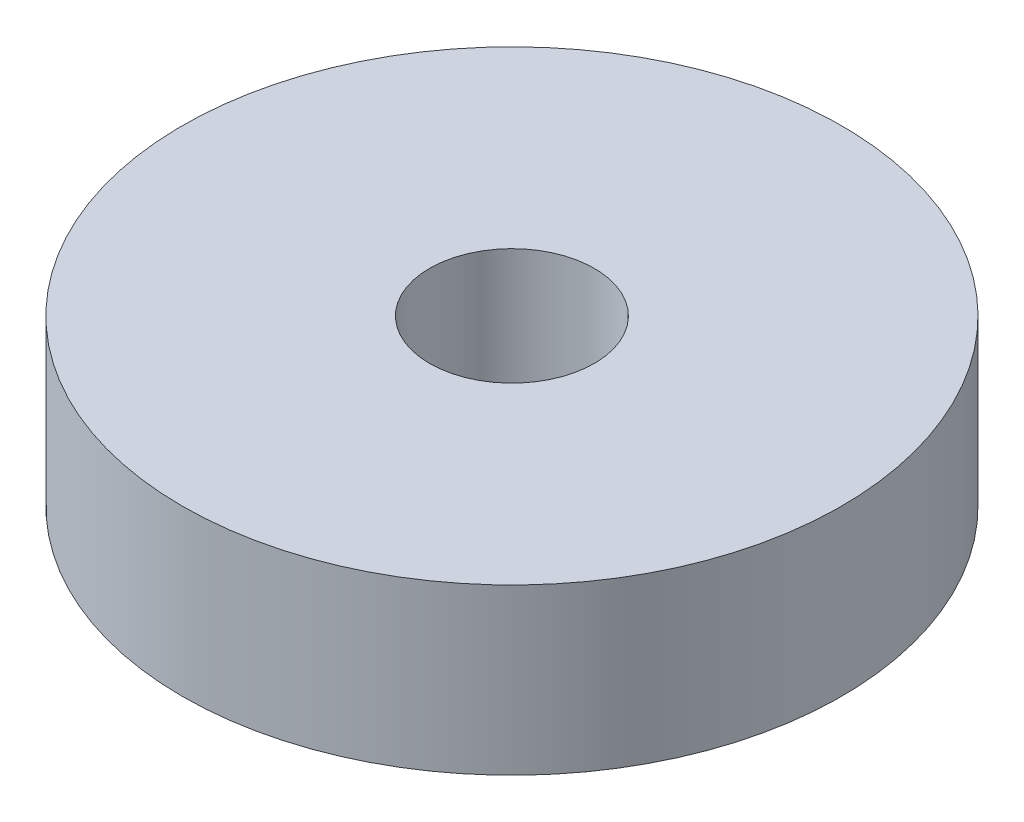
SolidWorks part; units mm, degrees
ref_plane "Front Plane" through (0, 0, 0) normal (0, 0, 1) x (1, 0, 0)
ref_plane "Top Plane" through (0, 0, 0) normal (0, 1, 0) x (1, 0, 0)
ref_plane "Right Plane" through (0, 0, 0) normal (1, 0, 0) x (0, 0, -1)
sketch "Sketch1" plane through (0, 0, 0) normal (0, 1, 0) x (1, 0, 0)
  circle A0 centre (0, 0) radius 2.5
  circle A1 centre (0, 0) radius 10
  dimension "D1" = 20
  dimension "D2" = 5
extrude "Boss-Extrude1" add sketch "Sketch1" along normal blind 5
